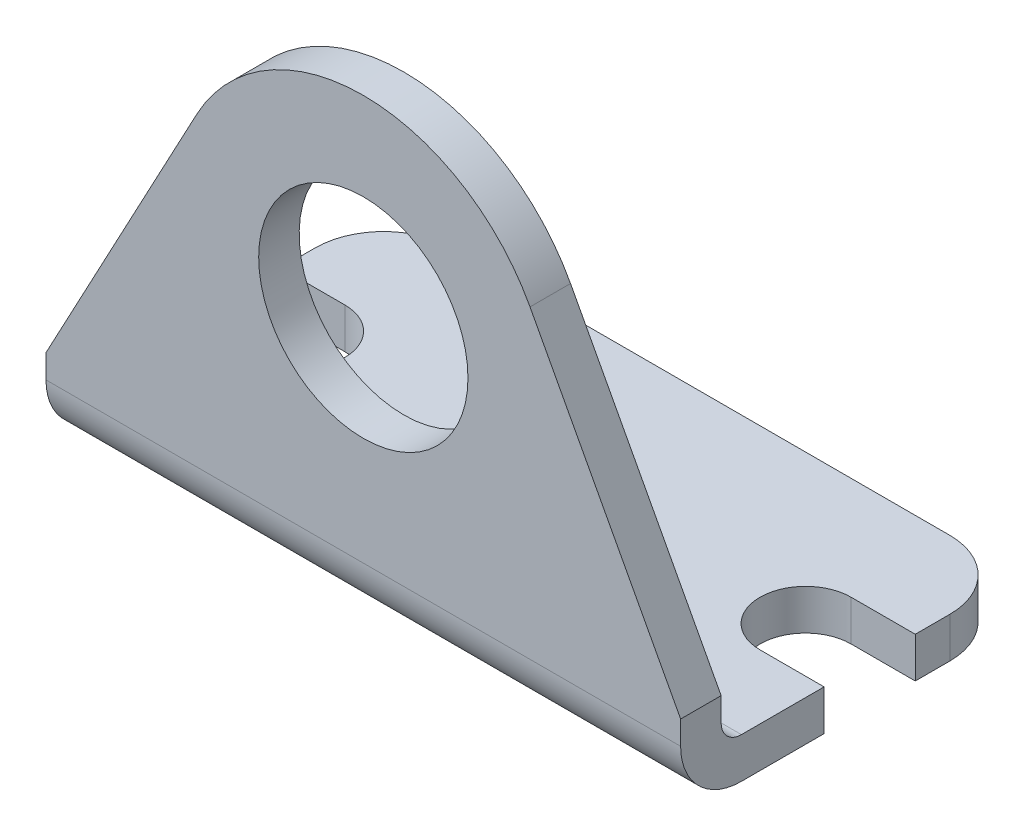
SolidWorks part; units mm, degrees
ref_plane "Front Plane" through (0, 0, 0) normal (0, 0, 1) x (1, 0, 0)
ref_plane "Top Plane" through (0, 0, 0) normal (0, 1, 0) x (1, 0, 0)
ref_plane "Right Plane" through (0, 0, 0) normal (1, 0, 0) x (0, 0, -1)
sketch "Sketch1" plane through (0, 0, 0) normal (0, 1, 0) x (1, 0, 0)
  line L0 (-23.876, 0) -> (23.876, 0) construction
  line L1 (0, 11.176) -> (0, -14.224) construction
  line L2 (-19.05, 3.429) -> (-23.876, 3.429)
  line L3 (-23.876, 3.429) -> (-23.876, -3.429)
  line L4 (-19.05, -3.429) -> (-23.876, -3.429)
  line L5 (19.05, 3.429) -> (23.876, 3.429)
  line L6 (23.876, 3.429) -> (23.876, -3.429)
  line L7 (19.05, -3.429) -> (23.876, -3.429)
  arc A0 (-19.05, -3.429) -> (-19.05, 3.429) centre (-19.05, 0) ccw
  arc A1 (19.05, 3.429) -> (19.05, -3.429) centre (19.05, 0) ccw
  dimension "Width" = 47.752
  dimension "Depth" = 25.4
  dimension "Hole Dia" = 6.858
  dimension "Hole Location" = 19.05
  dimension "D5" = 19.05
  dimension "HL" = 14.224
sketch "Sketch2" plane through (0, 0, 0) normal (0, 0, 1) x (1, 0, 0)
  line L0 (-23.876, 0) -> (23.876, 0)
  line L1 (23.876, 0) -> (23.876, 6.35)
  line L2 (23.876, 6.35) -> (12.5423, 27.5373)
  line L3 (-23.876, 0) -> (-23.876, 6.35)
  line L4 (-23.876, 6.35) -> (-12.5423, 27.5373)
  line L5 (0, 0) -> (0, 20.828) construction
  line L6 (-23.876, 3.048) -> (23.876, 3.048) construction
  arc A0 (-12.5423, 27.5373) -> (12.5423, 27.5373) centre (0, 20.828) cw
  circle A1 centre (0, 20.574) radius 7.874
  dimension "ID" = 15.748
  dimension "Radius" = 14.224
  dimension "C to C" = 20.574
  dimension "Height" = 35.052
  dimension "Thickness" = 3.048
  dimension "D5" = 6.35
sketch "Sketch3" plane through (0, 0, 0) normal (0, 0, 1) x (1, 0, 0)
  line L5 (-23.876, 0) -> (23.876, 0)
  line L6 (23.876, 0) -> (23.876, 6.35)
  line L7 (23.876, 6.35) -> (12.5423, 27.5373)
  line L8 (-12.5423, 27.5373) -> (-23.876, 6.35)
  line L9 (-23.876, 6.35) -> (-23.876, 0)
  line L10 (-23.876, 0) -> (23.876, 0)
  line L11 (23.876, 0) -> (23.876, 6.35)
  line L12 (23.876, 6.35) -> (12.5423, 27.5373)
  line L13 (-12.5423, 27.5373) -> (-23.876, 6.35)
  line L14 (-23.876, 6.35) -> (-23.876, 0)
  circle A1 centre (0, 20.574) radius 7.874
  circle A2 centre (0, 20.574) radius 7.874
  arc A3 (12.5423, 27.5373) -> (-12.5423, 27.5373) centre (0, 20.828) ccw
  arc A4 (12.5423, 27.5373) -> (-12.5423, 27.5373) centre (0, 20.828) ccw
  dimension "D1" = 0
  dimension "D2" = 0
extrude "Boss-Extrude1" add sketch "Sketch3" along normal up to vertex (14.224 mm away) and the other way up to vertex (11.176 mm away) up to point (0, 0, 14.224) other way up to point (0, 0, -11.176)
sketch "Sketch4" plane through (0, 0, 0) normal (0, 1, 0) x (1, 0, 0)
  line L0 (-23.876, 3.429) -> (-23.876, -3.429) construction
  line L1 (-19.05, -3.429) -> (-23.876, -3.429) construction
  line L2 (-19.05, 3.429) -> (-23.876, 3.429) construction
  line L3 (19.05, 3.429) -> (23.876, 3.429) construction
  line L4 (19.05, -3.429) -> (23.876, -3.429) construction
  line L6 (-23.876, 3.429) -> (-23.876, -3.429)
  line L7 (-19.05, -3.429) -> (-23.876, -3.429)
  line L8 (-19.05, 3.429) -> (-23.876, 3.429)
  line L9 (19.05, 3.429) -> (23.876, 3.429)
  line L10 (19.05, -3.429) -> (23.876, -3.429)
  line L12 (23.876, -3.429) -> (23.876, 3.429)
  arc A0 (-19.05, -3.429) -> (-19.05, 3.429) centre (-19.05, 0) ccw construction
  arc A1 (19.05, 3.429) -> (19.05, -3.429) centre (19.05, 0) ccw construction
  arc A2 (-19.05, -3.429) -> (-19.05, 3.429) centre (-19.05, 0) ccw
  arc A3 (19.05, 3.429) -> (19.05, -3.429) centre (19.05, 0) ccw
extrude "Cut-Extrude1" cut sketch "Sketch4" along normal through all
sketch "Sketch5" plane through (-23.876, 0, 0) normal (-1, 0, 0) x (0, 0, 1)
  line L0 (14.224, 27.5373) -> (14.224, 6.35) construction
  line L1 (-11.176, 35.052) -> (11.176, 35.052)
  line L2 (-11.176, 35.052) -> (-11.176, 3.048)
  line L3 (-11.176, 3.048) -> (9.652, 3.048)
  line L4 (11.176, 35.052) -> (11.176, 4.572)
  line L5 (-11.176, 6.35) -> (-11.176, 0) construction
  line L6 (14.224, 35.052) -> (-11.176, 35.052) construction
  line L7 (-11.176, 0) -> (14.224, 0) construction
  line L8 (14.224, 6.35) -> (14.224, 0) construction
  line L9 (9.652, 0) -> (14.224, 0)
  line L10 (14.224, 4.572) -> (14.224, 0)
  arc A0 (9.652, 3.048) -> (11.176, 4.572) centre (9.652, 4.572) ccw
  arc A1 (9.652, 0) -> (14.224, 4.572) centre (9.652, 4.572) ccw
  dimension "D3" = 1.524
  dimension "D4" = 4.572
  dimension "D1" = 3.048
  dimension "Thickness" = 3.048
extrude "Cut-Extrude2" cut sketch "Sketch5" against normal through all
fillet "Fillet1" radius 5.1435 2 edges at (-23.876, 1.524, -11.176) (23.876, 1.524, -11.176)
equation "\"D4@Sketch5\" = \"D1@Sketch5\"+\"D3@Sketch5\""
equation "\"D5@Sketch1\" = \"Hole Location@Sketch1\""
equation "\"D3@Sketch5\" = \"Thickness@Sketch5\"/2"
equation "\"D1@Fillet1\" = \"Hole Dia@Sketch1\"*.750"
equation "\"Thickness@Sketch5\" = \"Thickness@Sketch2\""
equation "\"D1@Sketch5\" = \"Thickness@Sketch5\""
